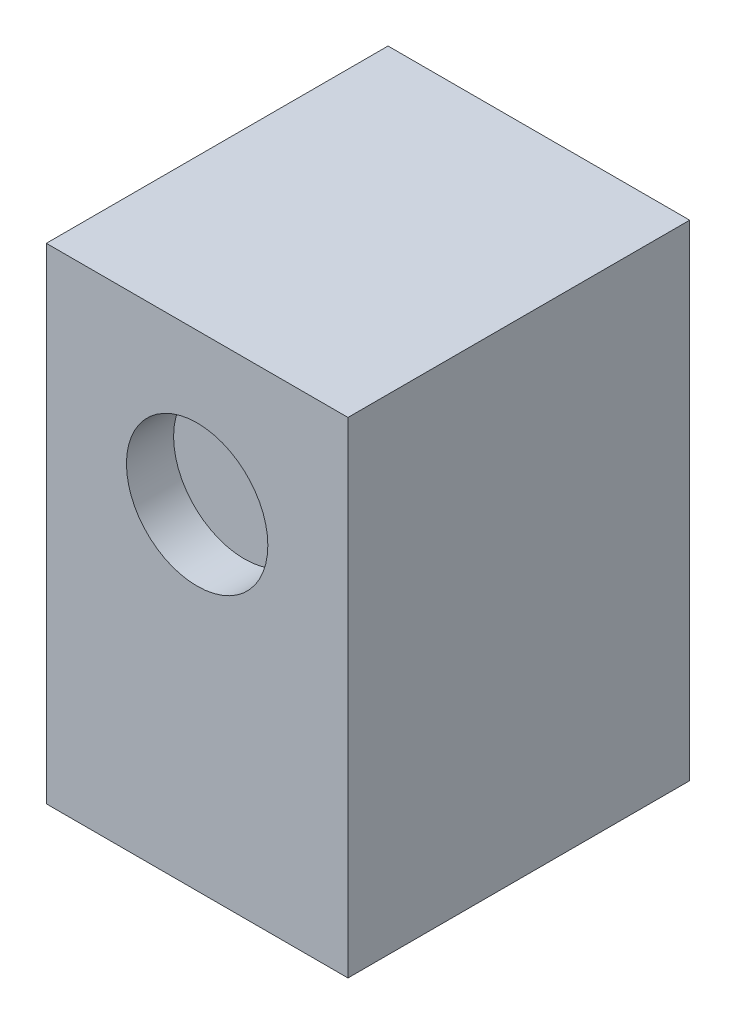
SolidWorks part; units mm, degrees
ref_plane "Front Plane" through (0, 0, 0) normal (0, 0, 1) x (1, 0, 0)
ref_plane "Top Plane" through (0, 0, 0) normal (0, 1, 0) x (1, 0, 0)
ref_plane "Right Plane" through (0, 0, 0) normal (1, 0, 0) x (0, 0, -1)
sketch "Sketch1" plane through (0, 0, 0) normal (0, 1, 0) x (1, 0, 0)
  line L1 (-32, -36.25) -> (32, -36.25)
  line L2 (-32, -36.25) -> (-32, 36.25)
  line L3 (-32, 36.25) -> (32, 36.25)
  line L4 (32, -36.25) -> (32, 36.25)
  line L5 (-32, -36.25) -> (32, 36.25) construction
  line L6 (-32, 36.25) -> (32, -36.25) construction
  point P0 (0, 0)
  dimension "D1" = 64
  dimension "D2" = 72.5
extrude "Boss-Extrude1" add sketch "Sketch1" along normal blind 103
sketch "Sketch2" plane through (0, 0, 36.25) normal (0, 0, 1) x (1, 0, 0)
  line L0 (-32, 103) -> (32, 103) construction
  line L1 (32, 103) -> (32, 39) construction
  line L2 (32, 103) -> (32, 0) construction
  line L3 (32, 39) -> (-32, 39) construction
  line L4 (-32, 103) -> (-32, 0) construction
  line L5 (-32, 39) -> (-32, 103) construction
  line L6 (-32, 103) -> (32, 39) construction
  line L7 (-32, 39) -> (32, 103) construction
  circle A0 centre (0, 71) radius 15
  dimension "D2" = 30
  dimension "D1" = 64
extrude "Cut-Extrude1" cut sketch "Sketch2" against normal blind 10
sketch "Sketch3" plane through (0, 0, 0) normal (0, -1, 0) x (1, 0, 0)
  line L0 (-32, 36.25) -> (32, -36.25) construction
  line L1 (32, 36.25) -> (-32, -36.25) construction
  circle A0 centre (0, 0) radius 15
  dimension "D1" = 30
extrude "Cut-Extrude2" cut sketch "Sketch3" against normal blind 10
ref_point "Point6"
ref_point "Point8"
